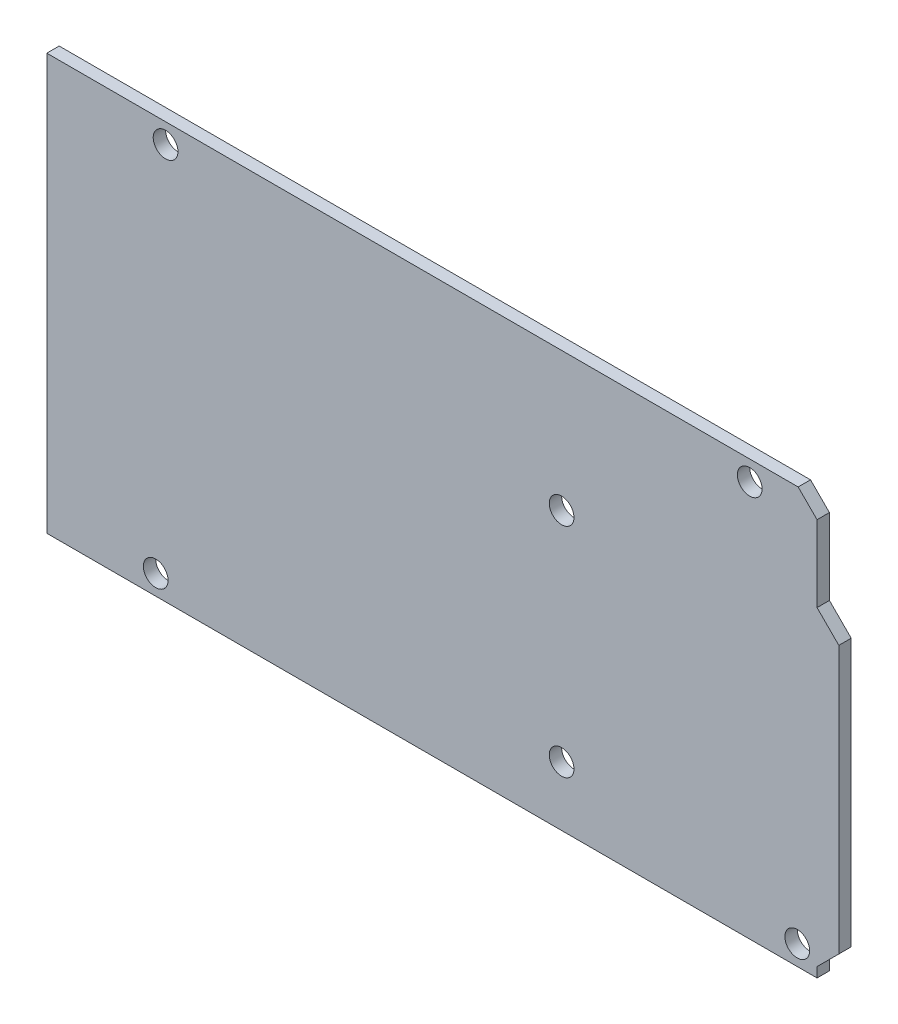
SolidWorks part; units mm, degrees
ref_plane "Front Plane" through (0, 0, 0) normal (0, 0, 1) x (1, 0, 0)
ref_plane "Top Plane" through (0, 0, 0) normal (0, 1, 0) x (1, 0, 0)
ref_plane "Right Plane" through (0, 0, 0) normal (1, 0, 0) x (0, 0, -1)
sketch "Sketch1" plane through (0, 0, 0) normal (0, 0, 1) x (1, 0, 0)
  line L0 (13.97, 2.54) -> (96.266, 2.54) construction
  line L1 (0, 0) -> (101.6, 0)
  line L2 (0, 0) -> (0, 53.34)
  line L3 (0, 53.34) -> (96.3813, 53.34)
  line L4 (101.6, 0) -> (101.6, 38.354)
  line L5 (66.04, 7.62) -> (66.04, 35.56) construction
  line L6 (15.24, 50.8) -> (90.17, 50.8) construction
  line L7 (98.806, 0) -> (98.806, 1.27)
  line L8 (98.806, 1.27) -> (101.6, 4.064)
  line L9 (96.3813, 53.34) -> (98.806, 50.9153)
  line L10 (98.806, 50.9153) -> (98.806, 41.148)
  line L11 (98.806, 41.148) -> (101.6, 38.354)
  circle A0 centre (15.24, 50.8) radius 1.5875
  circle A1 centre (13.97, 2.54) radius 1.5875
  circle A2 centre (90.17, 50.8) radius 1.5875
  circle A3 centre (96.266, 2.54) radius 1.5875
  circle A4 centre (66.04, 35.56) radius 1.5875
  circle A5 centre (66.04, 7.62) radius 1.5875
  dimension "D4" = 3.175
  dimension "D1" = 101.6
  dimension "D2" = 53.34
  dimension "D3" = 2.54
  dimension "D5" = 13.97
  dimension "D6" = 1.27
  dimension "D7" = 5.08
  dimension "D8" = 27.94
  dimension "D9" = 15.24
  dimension "D10" = 50.8
  dimension "D11" = 24.13
  dimension "D12" = 82.296
  dimension "D13" = 1.27
  dimension "D14" = 135
  dimension "D15" = 2.794
  dimension "D16" = 39.878
  dimension "D17" = 3.429
extrude "Boss-Extrude1" add sketch "Sketch1" along normal blind 1.5875 contours L11 L10 L9 L3 L2 L1 L7 L8 L4 A5 A4 A3 A2 A1 A0
